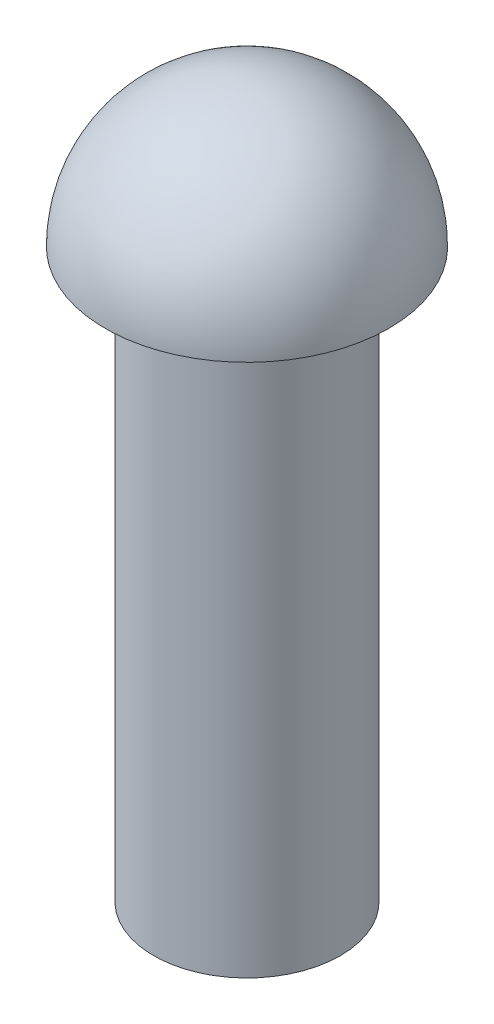
SolidWorks part; units mm, degrees
ref_plane "Front Plane" through (0, 0, 0) normal (0, 0, 1) x (1, 0, 0)
ref_plane "Top Plane" through (0, 0, 0) normal (0, 1, 0) x (1, 0, 0)
ref_plane "Right Plane" through (0, 0, 0) normal (1, 0, 0) x (0, 0, -1)
sketch "Sketch1" plane through (0, 0, 0) normal (0, 0, 1) x (1, 0, 0)
  line L0 (-15, 60) -> (-9.8734, 60)
  line L1 (0, 0) -> (-9.8734, 0)
  line L2 (0, 0) -> (0, 60)
  line L4 (-9.8734, 0) -> (-9.8734, 60)
  line L5 (0, 60) -> (0, 75)
  arc A0 (0, 75) -> (-15, 60) centre (0, 60) ccw
  dimension "D2" = 30
  dimension "D1" = 60
revolve "Revolve1" add sketch "Sketch1" angle 360 about L5
